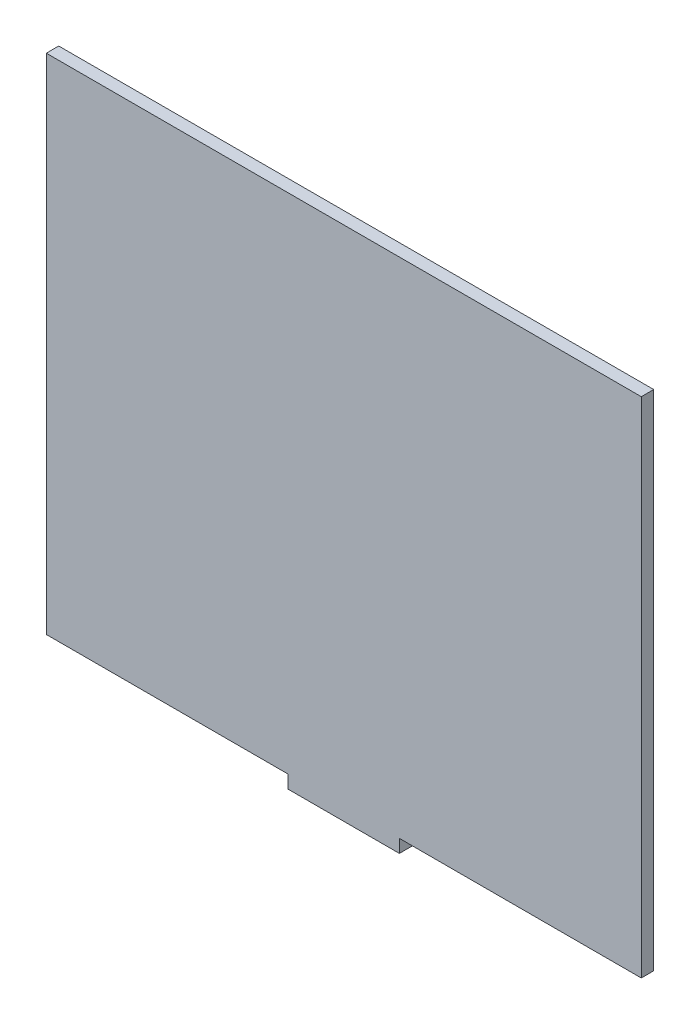
SolidWorks part; units mm, degrees
ref_plane "前视基准面" through (0, 0, 0) normal (0, 0, 1) x (1, 0, 0)
ref_plane "上视基准面" through (0, 0, 0) normal (0, 1, 0) x (1, 0, 0)
ref_plane "右视基准面" through (0, 0, 0) normal (1, 0, 0) x (0, 0, -1)
other "Configuration Table"
sketch "草图1" plane through (0, 0, 0) normal (0, 0, 1) x (1, 0, 0)
  line L0 (-8.5, -38.5) -> (-8.5, -40.5)
  line L1 (-45.5, 38.5) -> (45.5, 38.5)
  line L2 (-45.5, 38.5) -> (-45.5, -38.5)
  line L3 (-45.5, -38.5) -> (45.5, -38.5)
  line L4 (45.5, 38.5) -> (45.5, -38.5)
  line L5 (-45.5, 38.5) -> (45.5, -38.5) construction
  line L6 (-45.5, -38.5) -> (45.5, 38.5) construction
  line L7 (-8.5, -40.5) -> (8.5, -40.5)
  line L8 (8.5, -40.5) -> (8.5, -38.5)
  point P0 (0, 0)
  dimension "D1" = 77
  dimension "D2" = 91
  dimension "D3" = 2
  dimension "D4" = 37
  dimension "D5" = 37
extrude "凸台-拉伸1" add sketch "草图1" along normal blind 1.9 contours L4 L1 L2 L3 | L7 L8 L3 L0
